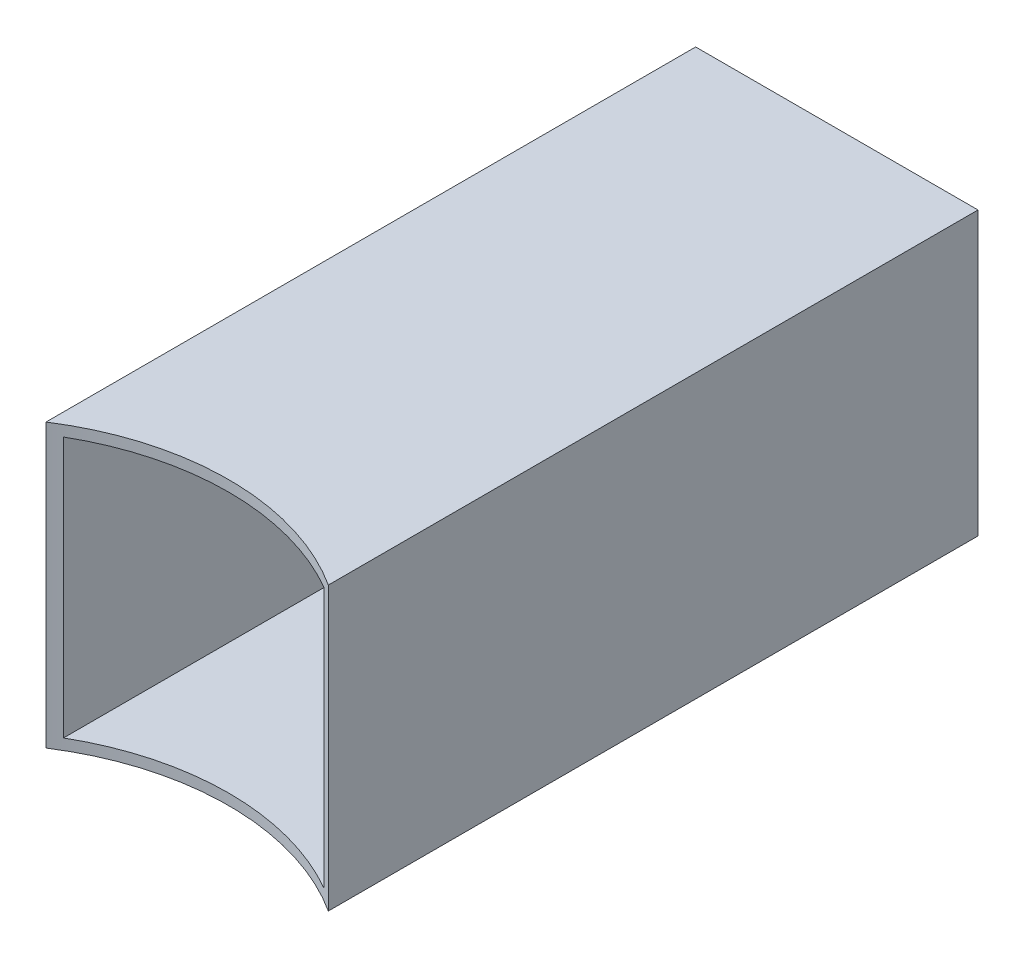
SolidWorks part; units mm, degrees
ref_plane "Alzado" through (0, 0, 0) normal (0, 0, 1) x (1, 0, 0)
ref_plane "Planta" through (0, 0, 0) normal (0, 1, 0) x (1, 0, 0)
ref_plane "Vista lateral" through (0, 0, 0) normal (1, 0, 0) x (0, 0, -1)
sketch "Croquis1" plane through (0, 0, 0) normal (0, 0, 1) x (1, 0, 0)
  line L1 (-6.5, 6.5) -> (6.5, 6.5)
  line L2 (-6.5, 6.5) -> (-6.5, -6.5)
  line L3 (-6.5, -6.5) -> (6.5, -6.5)
  line L4 (6.5, 6.5) -> (6.5, -6.5)
  line L5 (-6.5, 6.5) -> (6.5, -6.5) construction
  line L6 (-6.5, -6.5) -> (6.5, 6.5) construction
  point P0 (0, 0)
  dimension "D1" = 13
  dimension "D2" = 13
extrude "Saliente-Extruir1" add sketch "Croquis1" along normal blind 40
sketch "Croquis2" plane through (0, 0, 40) normal (0, 0, 1) x (1, 0, 0)
  line L1 (-6, 6) -> (6, 6)
  line L2 (-6, 6) -> (-6, -6)
  line L3 (-6, -6) -> (6, -6)
  line L4 (6, 6) -> (6, -6)
  line L5 (-6, 6) -> (6, -6) construction
  line L6 (-6, -6) -> (6, 6) construction
  point P0 (0, 0)
  dimension "D1" = 12
  dimension "D2" = 12
extrude "Cortar-Extruir1" cut sketch "Croquis2" against normal up to next
sketch "Croquis4" plane through (0, 6.5, 0) normal (0, 1, 0) x (1, 0, 0)
  line L0 (6.5, -40) -> (-6.5, -40) construction
  circle A0 centre (0, -40) radius 12
extrude "Cortar-Extruir3" cut sketch "Croquis4" against normal blind 26
